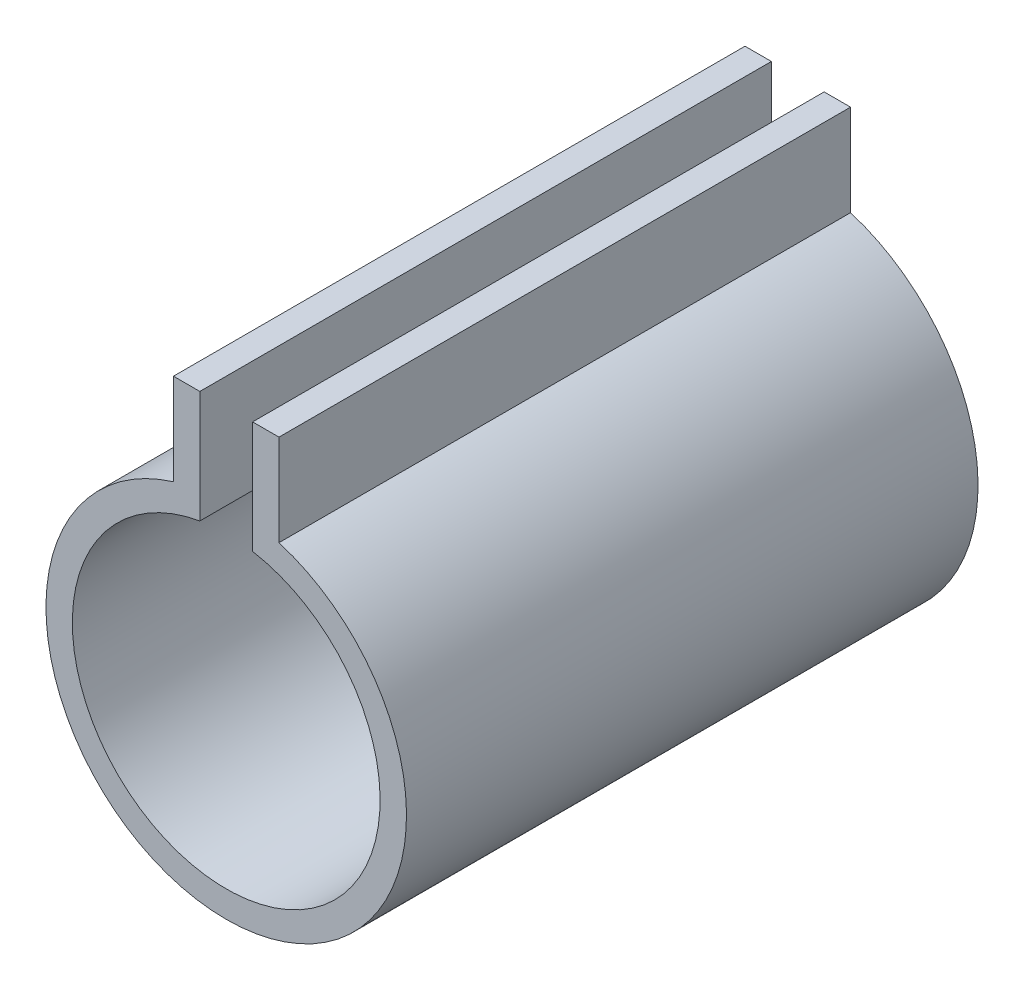
SolidWorks part; units mm, degrees
ref_plane "Front" through (0, 0, 0) normal (0, 0, 1) x (1, 0, 0)
ref_plane "Top" through (0, 0, 0) normal (0, 1, 0) x (1, 0, 0)
ref_plane "Right" through (0, 0, 0) normal (1, 0, 0) x (0, 0, -1)
sketch "Sketch1" plane through (0, 0, 0) normal (0, 0, 1) x (1, 0, 0)
  line L0 (0, 17.5) -> (0, 30) construction
  line L1 (3, 17.2409) -> (3, 30)
  line L2 (-3, 17.2409) -> (-3, 30)
  line L3 (6, 19.6023) -> (6, 30)
  line L4 (-6, 19.6023) -> (-6, 30)
  line L5 (-3, 30) -> (-6, 30)
  line L6 (3, 30) -> (6, 30)
  line L7 (6, 0) -> (6, 30) construction
  line L8 (3, 0) -> (3, 30) construction
  line L9 (0, 0) -> (0, 30) construction
  line L10 (-3, 0) -> (-3, 30) construction
  line L11 (-6, 0) -> (-6, 30) construction
  arc A0 (-3, 17.2409) -> (3, 17.2409) centre (0, 0) ccw
  arc A1 (-6, 19.6023) -> (6, 19.6023) centre (0, 0) ccw
  circle A2 centre (0, 0) radius 20.5 construction
  circle A3 centre (0, 0) radius 17.5 construction
  dimension "D1" = 35
  dimension "D3" = 30
  dimension "D2" = 3
  dimension "D4" = 3
  dimension "D5" = 3
  dimension "D6" = 3
  dimension "D7" = 3
extrude "Boss-Extrude1" add sketch "Sketch1" along normal blind 65
